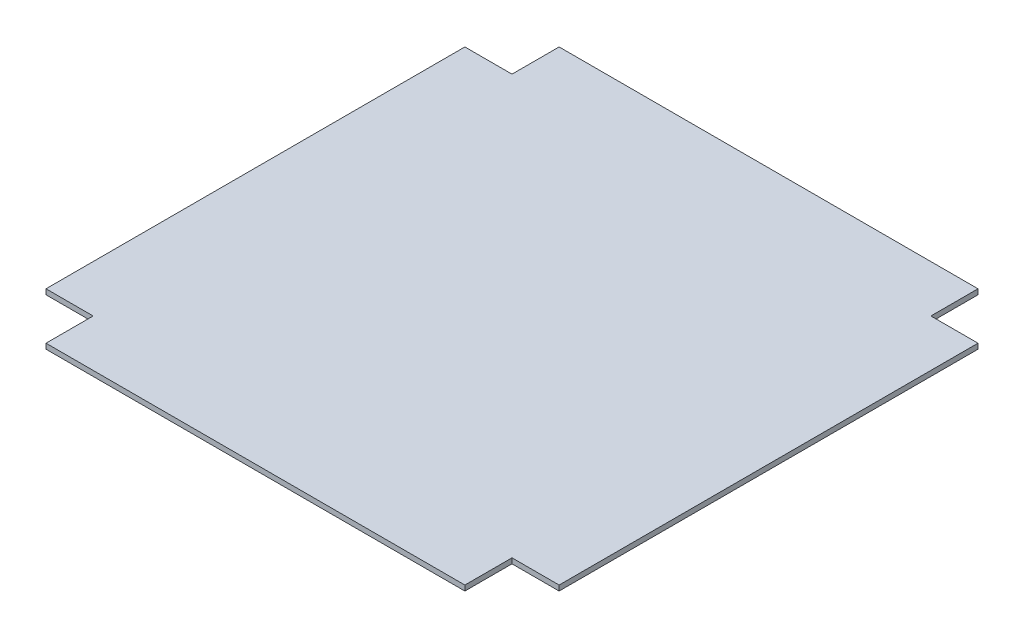
SolidWorks part; units mm, degrees
material "Acrylique (impact moyen-haut)"
ref_plane "Plan de face" through (0, 0, 0) normal (0, 0, 1) x (1, 0, 0)
ref_plane "Plan de dessus" through (0, 0, 0) normal (0, 1, 0) x (1, 0, 0)
ref_plane "Plan de droite" through (0, 0, 0) normal (1, 0, 0) x (0, 0, -1)
sketch "Esquisse1" plane through (0, 0, 0) normal (0, 1, 0) x (1, 0, 0)
  line L0 (-245, 200) -> (-200, 200)
  line L1 (-200, 245) -> (0, 245)
  line L2 (-245, 200) -> (-245, 0)
  line L5 (-200, 200) -> (-200, 245)
  line L10 (200, 245) -> (200, 200)
  line L11 (245, 200) -> (245, 0)
  line L12 (200, 245) -> (0, 245)
  line L13 (200, 200) -> (245, 200)
  line L16 (245, -200) -> (200, -200)
  line L17 (200, -245) -> (0, -245)
  line L18 (245, -200) -> (245, 0)
  line L19 (200, -200) -> (200, -245)
  line L21 (0, 292.4303) -> (0, -392.1939) construction
  line L22 (-200, -245) -> (-200, -200)
  line L23 (-245, -200) -> (-245, 0)
  line L24 (-200, -245) -> (0, -245)
  line L25 (-200, -200) -> (-245, -200)
  line L27 (292.4303, 0) -> (-392.1939, 0) construction
  point P40 (0, 0)
  dimension "D1" = 245
  dimension "D2" = 245
  dimension "D3" = 4
  dimension "D4" = 45
  dimension "D5" = 45
extrude "Boss.-Extru.1" add sketch "Esquisse1" along normal blind 5
